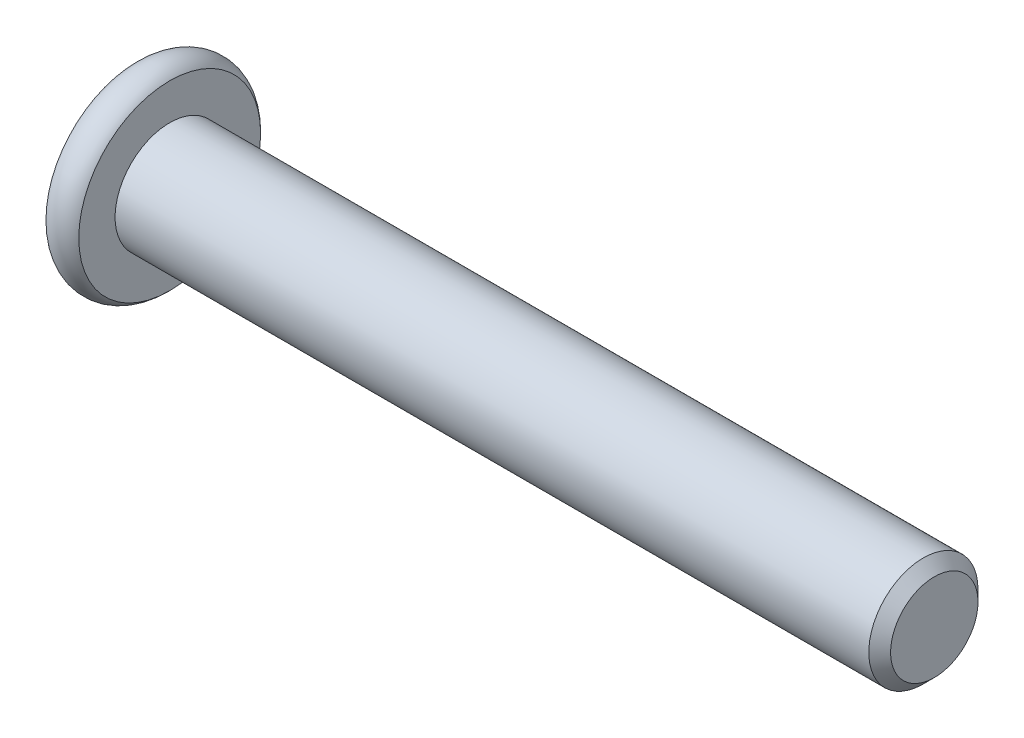
SolidWorks part; units mm, degrees
material "Plain Carbon Steel"
ref_plane "Front Plane" through (0, 0, 0) normal (0, 0, 1) x (1, 0, 0)
ref_plane "Top Plane" through (0, 0, 0) normal (0, 1, 0) x (1, 0, 0)
ref_plane "Right Plane" through (0, 0, 0) normal (1, 0, 0) x (0, 0, -1)
other "M5 x 15"
sketch "Sketch2" plane through (0, 0, 0) normal (1, 0, 0) x (0, 0, -1)
  circle A0 centre (0, 0) radius 2.5
  dimension "D1" = 5
extrude "Boss-Extrude1" add sketch "Sketch2" against normal blind 35
chamfer "Chamfer1" distance 0.5 angle 45 1 edges at (0, 0, -2.5)
sketch "Sketch6" plane through (0, 0, 0) normal (0, 0, 1) x (1, 0, 0)
  line L0 (-36.5, 0) -> (-36.5, 4.1614)
  line L1 (-36.5, 0) -> (-35, 0)
  line L2 (-35.75, 0) -> (-35.75, 3.5) construction
  line L6 (-35, 4.1614) -> (-35, 0)
  line L8 (-35, 0) -> (-14.6471, 0) construction
  line L10 (-35, 2.5) -> (-35, -2.5) construction
  arc A0 (-36.5, 4.1614) -> (-35, 4.1614) centre (-35.75, 3.5) cw
  dimension "D3" = 1
  dimension "D1" = 1.5
  dimension "D2" = 9
revolve "Revolve1" add sketch "Sketch6" angle 360 about L8
sketch "Sketch7" plane through (-36.5, 0, 0) normal (-1, 0, 0) x (0, 0, 1)
  line L1 (0, 1.7321) -> (-1.5, 0.866)
  line L2 (-1.5, 0.866) -> (-1.5, -0.866)
  line L3 (-1.5, -0.866) -> (0, -1.7321)
  line L4 (0, -1.7321) -> (1.5, -0.866)
  line L5 (1.5, -0.866) -> (1.5, 0.866)
  line L6 (1.5, 0.866) -> (0, 1.7321)
  circle A0 centre (0, 0) radius 1.5 construction
  dimension "D1" = 3
extrude "Cut-Extrude1" cut sketch "Sketch7" against normal blind 2.3
sketch "Sketch8" plane through (-36.5, 0, 0) normal (-1, 0, 0) x (0, 0, 1)
  circle A0 centre (0, 0) radius 1.7821
  dimension "D1" = 0.05
extrude "Cut-Extrude2" cut sketch "Sketch8" against normal blind 1 draft 45
